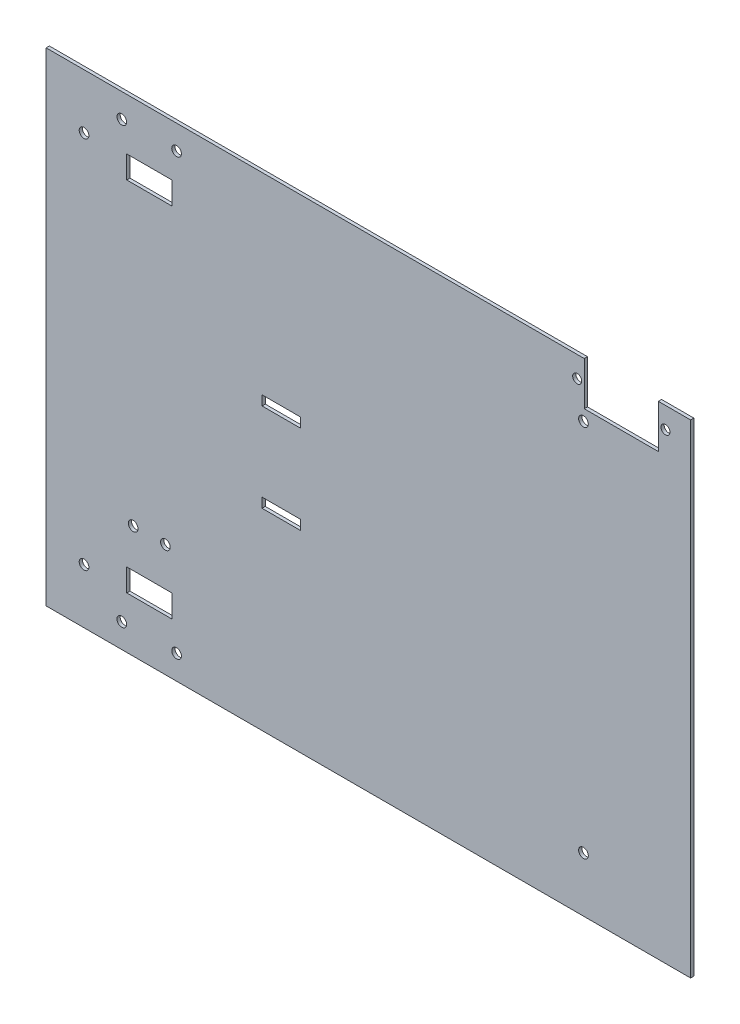
SolidWorks part; units mm, degrees
ref_plane "Front Plane" through (0, 0, 0) normal (0, 0, 1) x (1, 0, 0)
ref_plane "Top Plane" through (0, 0, 0) normal (0, 1, 0) x (1, 0, 0)
ref_plane "Right Plane" through (0, 0, 0) normal (1, 0, 0) x (0, 0, -1)
sketch "Sketch1" plane through (0, 0, 0) normal (0, 0, 1) x (1, 0, 0)
  line L1 (-100, 75) -> (100, 75)
  line L2 (-100, 75) -> (-100, -75)
  line L3 (-100, -75) -> (100, -75)
  line L4 (100, 75) -> (100, -75)
  line L5 (-100, 75) -> (100, -75) construction
  line L6 (-100, -75) -> (100, 75) construction
  point P0 (0, 0)
  dimension "D1" = 150
  dimension "D2" = 200
extrude "Boss-Extrude1" add sketch "Sketch1" along normal blind 1
sketch "Sketch2" plane through (0, 0, 1) normal (0, 0, 1) x (1, 0, 0)
  line L0 (-100, -75) -> (100, -75) construction
  line L1 (-75, -59) -> (-61, -59)
  line L2 (-75, -59) -> (-75, -52)
  line L3 (-75, -52) -> (-61, -52)
  line L4 (-61, -59) -> (-61, -52)
  line L5 (0, 0) -> (-128.0779, 0) construction
  line L6 (-100, 75) -> (-100, -75) construction
  line L7 (-75, 52) -> (-61, 52)
  line L8 (-61, 59) -> (-61, 52)
  line L9 (-75, 59) -> (-61, 59)
  line L10 (-75, 59) -> (-75, 52)
  line L12 (-33, -15.25) -> (-21, -15.25)
  line L13 (-33, -15.25) -> (-33, -12.25)
  line L14 (-33, -12.25) -> (-21, -12.25)
  line L15 (-21, -15.25) -> (-21, -12.25)
  line L19 (-68, -59) -> (-68, 77.2046) construction
  line L24 (-33, 12.25) -> (-21, 12.25)
  line L25 (-21, 15.25) -> (-21, 12.25)
  line L26 (-33, 15.25) -> (-21, 15.25)
  line L27 (-33, 15.25) -> (-33, 12.25)
  line L28 (100, 75) -> (-100, 75) construction
  line L33 (100, -75) -> (100, 75) construction
  line L34 (67, 75) -> (90, 75)
  line L35 (67, 75) -> (67, 61.5)
  line L36 (67, 61.5) -> (90, 61.5)
  line L37 (90, 75) -> (90, 61.5)
  circle A0 centre (-76.53, -67.5) radius 1.5
  circle A1 centre (-59.53, -67.5) radius 1.5
  circle A3 centre (-59.53, 67.5) radius 1.5
  circle A4 centre (-76.53, 67.5) radius 1.5
  circle A5 centre (-73, -40) radius 1.5
  circle A6 centre (-63, -40) radius 1.5
  circle A7 centre (-88.2535, -58) radius 1.5
  circle A8 centre (66.7465, -58) radius 1.5
  circle A9 centre (66.7465, 58) radius 1.5
  circle A10 centre (-88.2535, 58) radius 1.5
  circle A13 centre (64.8, 68.5) radius 1.4
  circle A14 centre (92.2, 68.5) radius 1.4
  point P13 (-68, -59)
  point P32 (66.7465, 58)
  dimension "D3" = 3
  dimension "D9" = 2
  dimension "D13" = 12.25
  dimension "D14" = 155
  dimension "D17" = 10
  dimension "D18" = 2.2
  dimension "D1" = 39
  dimension "D2" = 7
  dimension "D4" = 1.47
  dimension "D5" = 7.5
  dimension "D6" = 12
  dimension "D7" = 16
  dimension "D8" = 25
  dimension "D10" = 2
  dimension "D11" = 12
  dimension "D12" = 12
  dimension "D15" = 13.5
  dimension "D16" = 23
  dimension "D19" = 2.2
  dimension "D20" = 6.5
  dimension "D21" = 6.5
extrude "Cut-Extrude1" cut sketch "Sketch2" against normal blind 1
